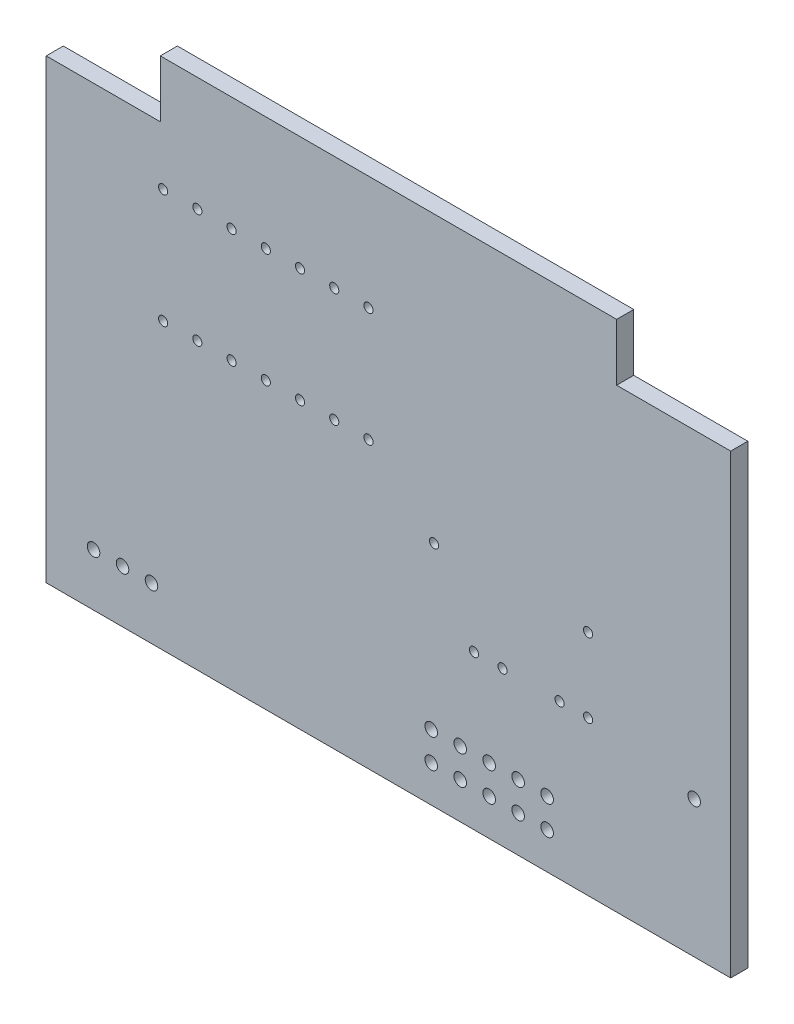
SolidWorks part; units mm, degrees
ref_plane "Спереди" through (0, 0, 0) normal (0, 0, 1) x (1, 0, 0)
ref_plane "Сверху" through (0, 0, 0) normal (0, 1, 0) x (1, 0, 0)
ref_plane "Справа" through (0, 0, 0) normal (1, 0, 0) x (0, 0, -1)
sketch "Эскиз1" plane through (0, 0, 0) normal (0, 0, 1) x (1, 0, 0)
  line L0 (0, 20) -> (0, 25)
  line L1 (-40, -20) -> (50, -20)
  line L2 (-40, -20) -> (-40, 20)
  line L3 (-40, 20) -> (0, 20)
  line L4 (50, -20) -> (50, 20)
  line L5 (0, 25) -> (40, 25)
  line L6 (40, 25) -> (40, 20)
  line L7 (40, 20) -> (50, 20)
  dimension "D1" = 90
  dimension "D2" = 40
  dimension "D3" = 40
  dimension "D4" = 40
  dimension "D5" = 5
  dimension "D6" = 20
extrude "Вытянуть1" add sketch "Эскиз1" along normal blind 1.5
sketch "Эскиз2" plane through (0, 0, 1.5) normal (0, 0, 1) x (1, 0, 0)
  line L0 (50, -20) -> (50, 20) construction
  line L1 (-40, -20) -> (50, -20) construction
  line L3 (-40, -20) -> (50, -20) construction
  line L4 (0, 25) -> (0, 20) construction
  circle A0 centre (-5.85, -15.4) radius 0.55
  circle A1 centre (-0.77, -15.4) radius 0.55
  circle A2 centre (-3.31, -15.4) radius 0.55
  circle A3 centre (23.75, -14.25) radius 0.55
  circle A4 centre (23.75, -16.79) radius 0.55
  circle A5 centre (26.29, -14.25) radius 0.55
  circle A6 centre (26.29, -16.79) radius 0.55
  circle A7 centre (28.83, -14.25) radius 0.55
  circle A8 centre (28.83, -16.79) radius 0.55
  circle A9 centre (31.37, -14.25) radius 0.55
  circle A10 centre (31.37, -16.79) radius 0.55
  circle A11 centre (33.91, -14.25) radius 0.55
  circle A12 centre (33.91, -16.79) radius 0.55
  dimension "D1" = 5.08
  dimension "D3" = 4.6
  dimension "D4" = 1.1
  dimension "D5" = 2.54
  dimension "D8" = 1.1
  dimension "D9" = 2.54
  dimension "D11" = 2.54
  dimension "D2" = 23.75
  dimension "D6" = 5.75
  dimension "D7" = 55.85
  dimension "D10" = 5.75
extrude "Вырез-Вытянуть1" cut sketch "Эскиз2" against normal blind 1.5
sketch "Эскиз3" plane through (0, 0, 1.5) normal (0, 0, 1) x (1, 0, 0)
  line L2 (0.25, 15) -> (0.25, 2.8182) construction
  line L3 (-40, -20) -> (50, -20) construction
  line L4 (0.25, 15) -> (28.1359, 15) construction
  line L6 (3.25, 15) -> (3.25, 2.8182) construction
  line L7 (6.25, 15) -> (6.25, 2.8182) construction
  line L8 (9.25, 15) -> (9.25, 2.8182) construction
  line L9 (12.25, 15) -> (12.25, 2.8182) construction
  line L10 (15.25, 15) -> (15.25, 2.8182) construction
  line L11 (18.25, 15) -> (18.25, 2.8182) construction
  line L12 (35, -6.5) -> (38.6778, -6.5) construction
  line L13 (-40, -20) -> (50, -20) construction
  line L14 (27.5, -6.5) -> (-16.1369, -6.5) construction
  line L15 (0, 25) -> (0, 20) construction
  line L20 (28.9777, 15) -> (21.3084, 15) construction
  line L34 (35, -6.5) -> (35, -5.3412) construction
  line L36 (27.5, -6.5) -> (27.5, -19) construction
  circle A0 centre (37.5, -6.5) radius 0.4
  circle A1 centre (30, -6.5) radius 0.4
  circle A12 centre (0.25, 15) radius 0.4
  circle A13 centre (0.25, 5) radius 0.4
  circle A16 centre (3.25, 15) radius 0.4
  circle A17 centre (3.25, 5) radius 0.4
  circle A18 centre (6.25, 15) radius 0.4
  circle A19 centre (6.25, 5) radius 0.4
  circle A20 centre (9.25, 15) radius 0.4
  circle A21 centre (9.25, 5) radius 0.4
  circle A22 centre (12.25, 15) radius 0.4
  circle A23 centre (12.25, 5) radius 0.4
  circle A42 centre (15.25, 15) radius 0.4
  circle A51 centre (15.25, 5) radius 0.4
  circle A52 centre (18.25, 15) radius 0.4
  circle A53 centre (18.25, 5) radius 0.4
  circle A71 centre (35, -6.5) radius 0.4
  circle A73 centre (27.5, -6.5) radius 0.4
  dimension "D2" = 3
  dimension "D3" = 0.8
  dimension "D15" = 35
  dimension "D16" = 0.25
  dimension "D40" = 10
  dimension "D41" = 10
  dimension "D5" = 2.5
  dimension "D7" = 35
  dimension "D8" = 13.5
  dimension "D9" = 2.5
  dimension "D17" = 27.5
  dimension "D18" = 3
  dimension "D6" = 13.5
  dimension "D10" = 3
  dimension "D11" = 3
  dimension "D12" = 3
  dimension "D13" = 3
  dimension "D14" = 3
extrude "Вырез-Вытянуть2" cut sketch "Эскиз3" against normal blind 10
sketch "Эскиз6" plane through (0, 0, 1.5) normal (0, 0, 1) x (1, 0, 0)
  line L3 (-40, -20) -> (50, -20) construction
  line L4 (-40, -20) -> (50, -20) construction
  line L5 (50, -20) -> (50, 20) construction
  circle A4 centre (24, 0) radius 0.4
  circle A7 centre (37.5, 0) radius 0.4
  dimension "D9" = 26
  dimension "D8" = 20
  dimension "D14" = 20
  dimension "D15" = 12.5
extrude "Вырез-Вытянуть4" cut sketch "Эскиз6" against normal blind 10
sketch "Эскиз7" plane through (0, 0, 0) normal (0, 0, -1) x (-1, 0, 0)
  line L0 (0, 25) -> (0, 20) construction
  line L1 (10, -30.6096) -> (42.7242, -30.6096)
  line L2 (10, -30.6096) -> (10, 28.9507)
  line L3 (10, 28.9507) -> (42.7242, 28.9507)
  line L4 (42.7242, -30.6096) -> (42.7242, 28.9507)
  dimension "D1" = 10
extrude "Вырез-Вытянуть5" cut sketch "Эскиз7" against normal blind 10
sketch "Эскиз8" plane through (0, 0, 1.5) normal (0, 0, 1) x (1, 0, 0)
  line L0 (50, -20) -> (50, 20) construction
  line L1 (-10, -20) -> (50, -20) construction
  circle A0 centre (46.8, -8) radius 0.55
  dimension "D1" = 1.1
  dimension "D2" = 3.2
  dimension "D3" = 12
extrude "Вырез-Вытянуть6" cut sketch "Эскиз8" against normal blind 10
